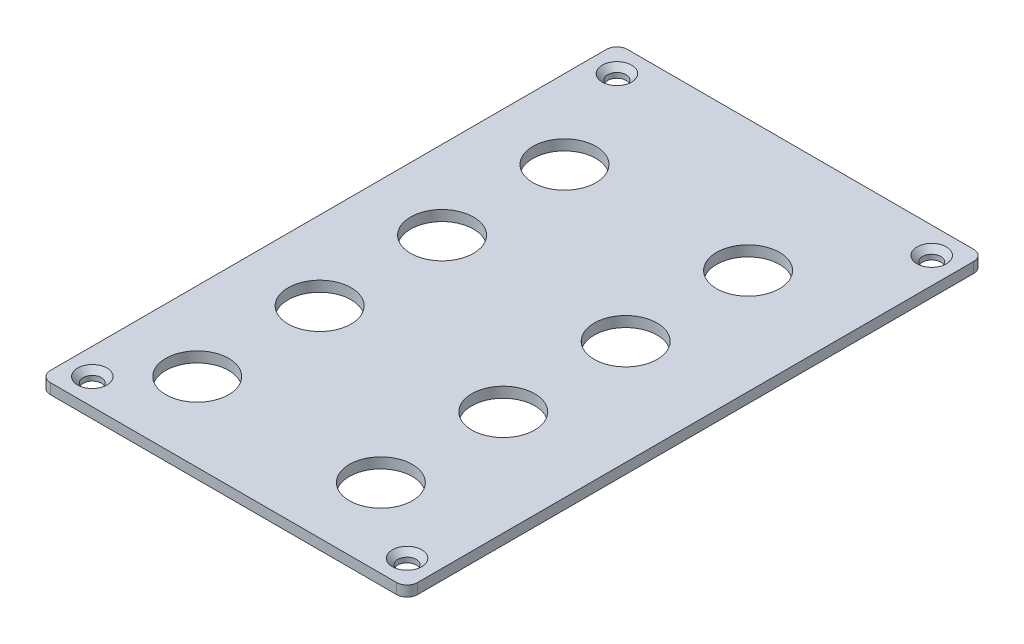
SolidWorks part; units mm, degrees
ref_plane "Front Plane" through (0, 0, 0) normal (0, 0, 1) x (1, 0, 0)
ref_plane "Top Plane" through (0, 0, 0) normal (0, 1, 0) x (1, 0, 0)
ref_plane "Right Plane" through (0, 0, 0) normal (1, 0, 0) x (0, 0, -1)
sketch "Face Plate" plane through (0, 0, 0) normal (0, 1, 0) x (1, 0, 0)
  line L1 (35, -55) -> (-35, -55)
  line L2 (35, -55) -> (35, 55)
  line L3 (35, 55) -> (-35, 55)
  line L4 (-35, -55) -> (-35, 55)
  line L5 (35, -55) -> (-35, 55) construction
  line L6 (35, 55) -> (-35, -55) construction
  point P0 (0, 0)
  dimension "D1" = 70
  dimension "D2" = 110
extrude "Face Plate Ext" add sketch "Face Plate" along normal blind 2
sketch "Buttons" plane through (0, 2, 0) normal (0, 1, 0) x (1, 0, 0)
  line L0 (35, -55) -> (35, 55) construction
  line L1 (-35, -55) -> (35, -55) construction
  line L5 (-35, 55) -> (-35, -55) construction
  line L6 (35, 55) -> (-35, 55) construction
  line L8 (-20, 30) -> (-20, -40) construction
  line L10 (0, 0) -> (0, 17.9718) construction
  circle A0 centre (-20, 30) radius 6
  circle A1 centre (15, 30) radius 6
  circle A2 centre (-20, 6.6667) radius 6
  circle A3 centre (15, 6.6667) radius 6
  circle A4 centre (-20, -16.6667) radius 6
  circle A5 centre (-20, -40) radius 6
  circle A6 centre (15, -16.6667) radius 6
  circle A7 centre (15, -40) radius 6
  dimension "D6" = 25
  dimension "D7" = 12
  dimension "D5" = 15
  dimension "D2" = 20
  dimension "D3" = 12
  dimension "D4" = 15
  dimension "D11" = 23.3333
  dimension "D13" = 12
  dimension "D14" = 12
  dimension "D8" = 23.3333
  dimension "D10" = 70
  dimension "D12" = 23.3333
extrude "Buttons CUT" cut sketch "Buttons" against normal blind 10
sketch "M3 Top Screw" plane through (0, 2, 0) normal (0, 1, 0) x (1, 0, 0)
  line L0 (-35, 55) -> (-35, -55) construction
  line L1 (35, 55) -> (-35, 55) construction
  line L2 (35, -55) -> (35, 55) construction
  line L3 (-35, -55) -> (35, -55) construction
  circle A0 centre (-30, 50) radius 1.75
  circle A1 centre (30, 50) radius 1.75
  circle A2 centre (-30, -50) radius 1.75
  circle A3 centre (30, -50) radius 1.75
  dimension "D1" = 3.5
  dimension "D2" = 5
  dimension "D3" = 5
  dimension "D4" = 5
  dimension "D5" = 5
extrude "M3 Top Screw CUT" cut sketch "M3 Top Screw" against normal blind 10
sketch "M3 Head Top" plane through (0, 2, 0) normal (0, 1, 0) x (1, 0, 0)
  circle A0 centre (-30, 50) radius 2.8
  circle A1 centre (30, 50) radius 2.8
  circle A2 centre (30, -50) radius 2.8
  circle A3 centre (-30, -50) radius 2.8
  dimension "D1" = 5.6
extrude "M3 Head Top CUT" cut sketch "M3 Head Top" against normal blind 10 draft 45
fillet "Fillet1" radius 2 1 edges at (-35, 1, -55)
fillet "Fillet2" radius 2 1 edges at (35, 1, -55)
fillet "Fillet3" radius 2 1 edges at (35, 1, 55)
fillet "Fillet4" radius 2 1 edges at (-35, 1, 55)
equation "\"SPACER_LEFT\" = 15"
equation "\"ENCODER\"=7.1"
equation "\"SCREW_M3\"=3.5"
equation "\"D1@M3 Top Screw\"=\"SCREW_M3\""
equation "\"SPACER_COVER_SCREW\"=5"
equation "\"D2@M3 Top Screw\"=\"SPACER_COVER_SCREW\""
equation "\"D3@M3 Top Screw\"=\"SPACER_COVER_SCREW\""
equation "\"D4@M3 Top Screw\"=\"SPACER_COVER_SCREW\""
equation "\"D5@M3 Top Screw\"=\"SPACER_COVER_SCREW\""
equation "\"SCREW_M3_HEAD\"=5.6"
equation "\"D1@M3 Head Top\"=\"SCREW_M3_HEAD\""
equation "\"BUTTON_PUSH\"=12"
equation "\"D3@Buttons\"=\"BUTTON_PUSH\""
equation "\"D5@Buttons\" = \"SPACER_LEFT\""
equation "\"SPACER_TOP\" = 25"
equation "\"D6@Buttons\"=\"SPACER_TOP\""
equation "\"SPACER_THIRD\"= \"D10@Buttons\" / 3"
equation "\"SPACER_FOURTH\"= \"D10@Buttons\" / 4"
equation "\"D8@Buttons\"=\"SPACER_THIRD\""
equation "\"D11@Buttons\"=\"SPACER_THIRD\""
equation "\"D12@Buttons\"=\"SPACER_THIRD\""
equation "\"D13@Buttons\"=\"BUTTON_PUSH\""
equation "\"D14@Buttons\"=\"BUTTON_PUSH\""
equation "\"SPACER_RIGHT\"= 20"
equation "\"D2@Buttons\"=\"SPACER_RIGHT\""
equation "\"SPACER_BOTTOM\"= 15"
equation "\"D4@Buttons\"=\"SPACER_BOTTOM\""
equation "\"BUTTON_TOGGLE\"= 12"
equation "\"D7@Buttons\"=\"BUTTON_TOGGLE\""
